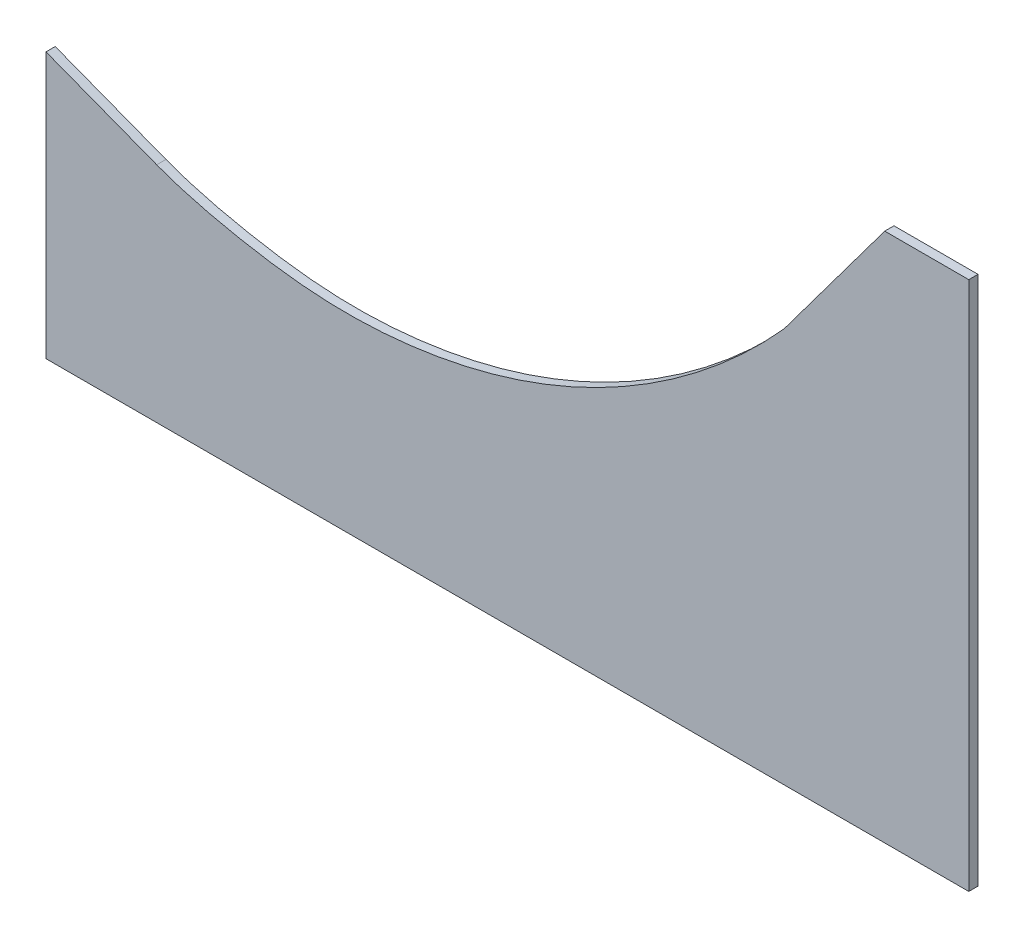
SolidWorks part; units mm, degrees
ref_plane "Přední rovina" through (0, 0, 0) normal (0, 0, 1) x (1, 0, 0)
ref_plane "Horní rovina" through (0, 0, 0) normal (0, 1, 0) x (1, 0, 0)
ref_plane "Pravá rovina" through (0, 0, 0) normal (1, 0, 0) x (0, 0, -1)
sketch "Skica1" plane through (0, 0, 0) normal (0, 0, 1) x (1, 0, 0)
  line L0 (-18, 24.2027) -> (-30, 28.7992)
  line L1 (-30, 0) -> (-30, 28.7992)
  line L2 (70, 0) -> (70, 57.4213)
  line L3 (60.8931, 57.4213) -> (50, 42.8155)
  line L4 (70, 0) -> (-30, 0)
  line L5 (70, 57.4213) -> (60.8931, 57.4213)
  spline S0 degree 3 poles (-18, 24.2027) (-15.421, 23.2149) (-9.4392, 21.7094) (-0.0498, 20.3049) (10.1152, 20.7814) (20.267, 22.9946) (34.6778, 28.8766) (44.3506, 36.4904) (50, 42.8155) knots 0 0 0 0 0.110931 0.245725 0.379434 0.516154 0.660347 1 1 1 1
extrude "Přidat vysunutím1" add sketch "Skica1" along normal blind 1
